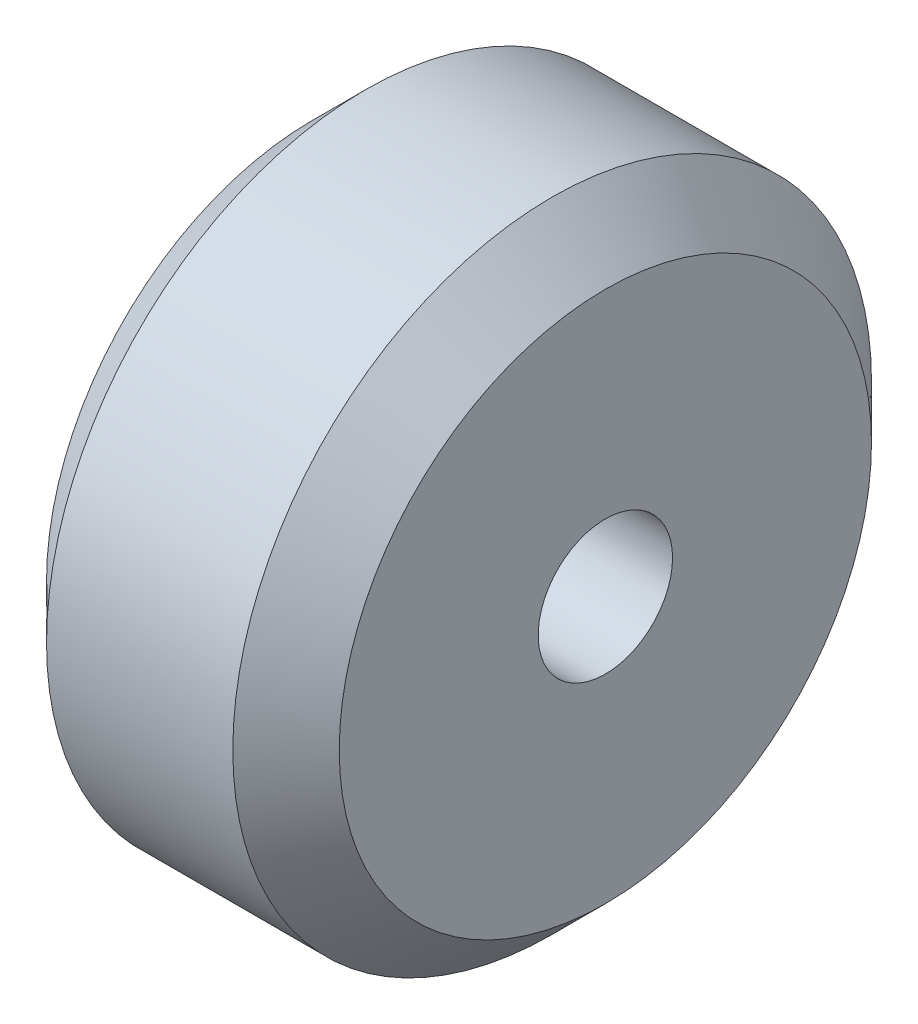
SolidWorks part; units mm, degrees
ref_plane "Front" through (0, 0, 0) normal (0, 0, 1) x (1, 0, 0)
ref_plane "Top" through (0, 0, 0) normal (0, 1, 0) x (1, 0, 0)
ref_plane "Right" through (0, 0, 0) normal (1, 0, 0) x (0, 0, -1)
sketch "Sketch1" plane through (0, 0, 0) normal (1, 0, 0) x (0, 0, -1)
  circle A0 centre (0, 0) radius 12
  circle A1 centre (0, 0) radius 2.525
  dimension "D1" = 24
  dimension "D2" = 5.05
extrude "Boss-Extrude1" add sketch "Sketch1" along normal blind 11
chamfer "Chamfer1" distance 2 angle 45 2 edges at (0, 0, -12) (11, 0, -12)
